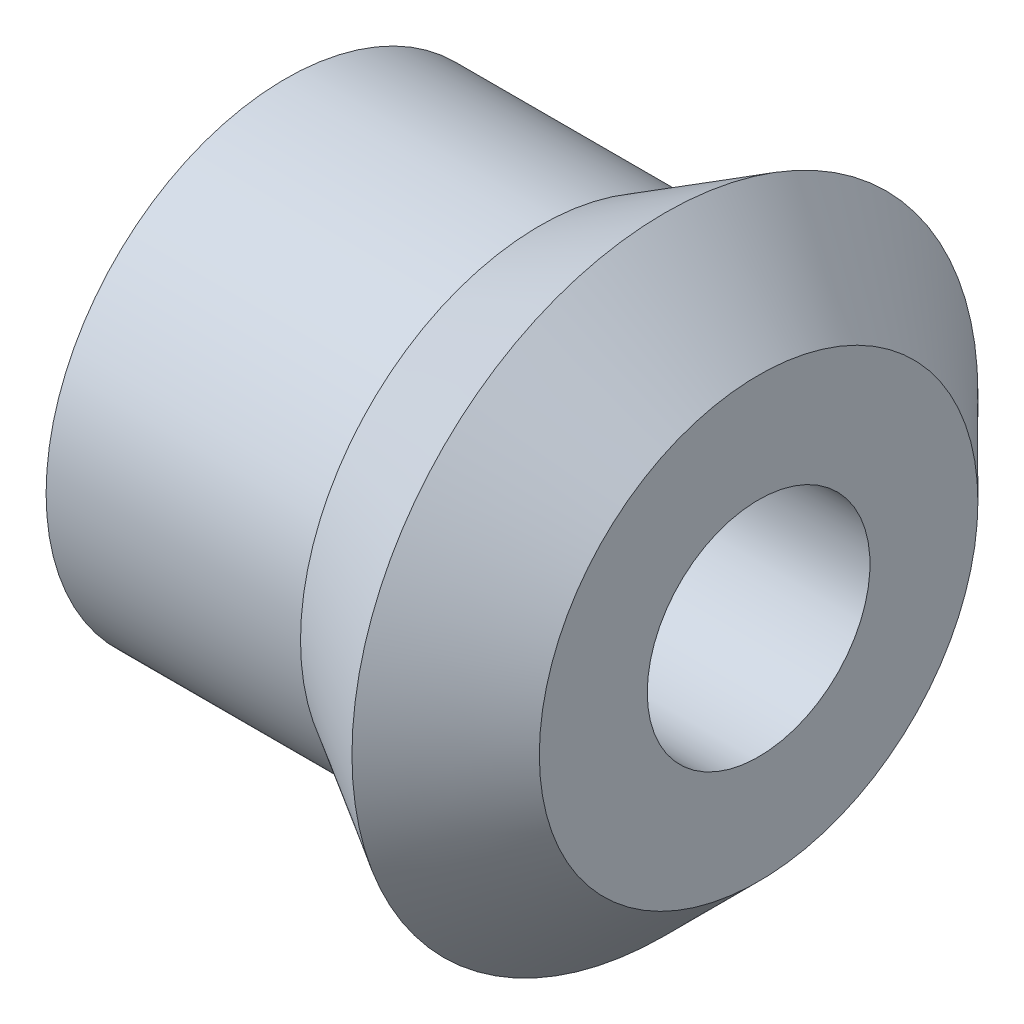
SolidWorks part; units mm, degrees
ref_plane "Front Plane" through (0, 0, 0) normal (0, 0, 1) x (1, 0, 0)
ref_plane "Top Plane" through (0, 0, 0) normal (0, 1, 0) x (1, 0, 0)
ref_plane "Right Plane" through (0, 0, 0) normal (1, 0, 0) x (0, 0, -1)
sketch "Sketch1" plane through (0, 0, 0) normal (0, 0, 1) x (1, 0, 0)
  line L0 (1.5883, 4.775) -> (-0.4517, 6.815)
  line L1 (-8.7117, 5.215) -> (-3.1717, 5.215)
  line L2 (-8.7117, 2.425) -> (-8.7117, 5.215)
  line L3 (-22.2616, 0) -> (68.45, 0) construction
  line L4 (1.5883, 2.425) -> (1.5883, 4.775)
  line L5 (-0.4517, 6.815) -> (-3.1717, 5.215)
  line L6 (-8.7117, 2.425) -> (1.5883, 2.425)
  dimension "D1" = 2.425
  dimension "D2" = 4.775
  dimension "D3" = 6.815
  dimension "D4" = 10.3
  dimension "D5" = 5.54
  dimension "D6" = 5.215
  dimension "D7" = 135
revolve "Revolve1" add sketch "Sketch1" angle 360 about L3
